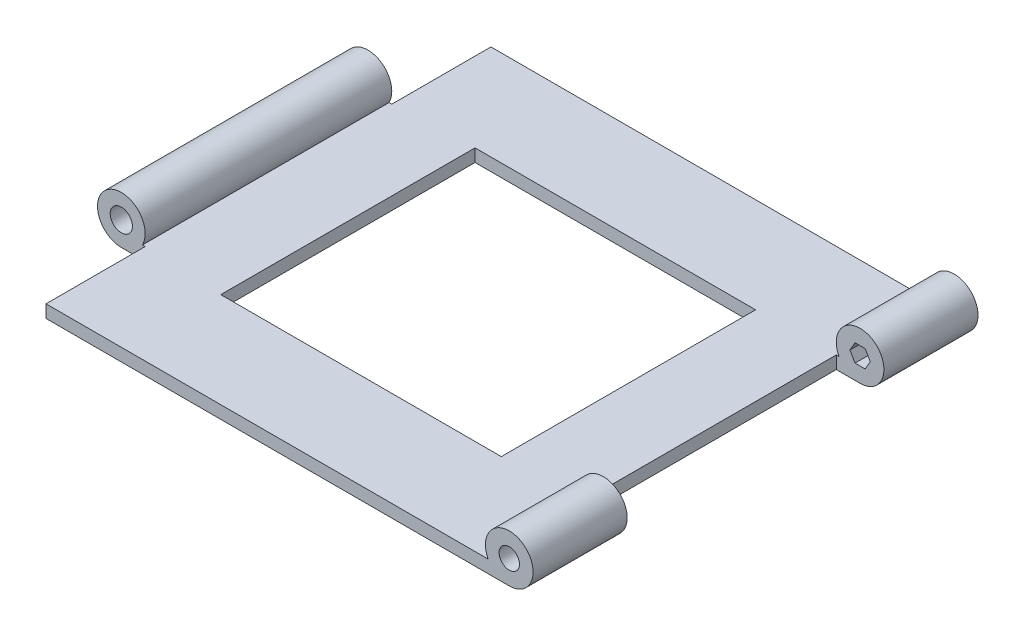
SolidWorks part; units mm, degrees
ref_plane "前视基准面" through (0, 0, 0) normal (0, 0, 1) x (1, 0, 0)
ref_plane "上视基准面" through (0, 0, 0) normal (0, 1, 0) x (1, 0, 0)
ref_plane "右视基准面" through (0, 0, 0) normal (1, 0, 0) x (0, 0, -1)
other "Configuration Table"
sketch "草图1" plane through (0, 0, 0) normal (0, 0, 1) x (1, 0, 0)
  line L0 (-77.4797, -5.3875) -> (75.7868, -5.3875)
  line L2 (69.1535, -1.3875) -> (-70.8465, -1.3875)
  line L4 (77.3868, 4.8838) -> (74.1868, 4.8838)
  line L5 (74.1868, 4.8838) -> (72.5868, 2.1125)
  line L6 (72.5868, 2.1125) -> (74.1868, -0.6588)
  line L7 (74.1868, -0.6588) -> (77.3868, -0.6588)
  line L8 (77.3868, -0.6588) -> (78.9868, 2.1125)
  line L9 (78.9868, 2.1125) -> (77.3868, 4.8838)
  arc A0 (-70.8465, -1.3875) -> (-77.4797, -5.3875) centre (-77.4797, 2.1125) ccw
  arc A1 (75.7868, -5.3875) -> (69.1535, -1.3875) centre (75.7868, 2.1125) ccw
  circle A2 centre (-77.4797, 2.1125) radius 3.5
  circle A3 centre (75.7868, 2.1125) radius 3.2 construction
  dimension "D1" = 4
  dimension "D2" = 7
  dimension "D3" = 6.4
  dimension "D4" = 4
  dimension "D6" = 4.3
  dimension "D5" = 140
extrude "凸台-拉伸1" add sketch "草图1" against normal blind 140
ref_plane "基准面1" through (-69.9797, 0, 0) normal (1, 0, 0) x (0, 0, -1)
sketch "草图2" plane through (-69.9797, 0, 0) normal (1, 0, 0) x (0, 0, -1)
  line L0 (140, 9.6125) -> (0, 9.6125) construction
  line L1 (0, -7.8675) -> (31.2, -7.8675)
  line L2 (0, -7.8675) -> (0, 9.6125)
  line L3 (0, 9.6125) -> (31.2, 9.6125)
  line L4 (31.2, -7.8675) -> (31.2, 9.6125)
  line L5 (140, 9.6125) -> (0, 9.6125) construction
  line L6 (70, 9.6125) -> (70, -10.9902) construction
  line L7 (140, 9.6125) -> (108.8, 9.6125)
  line L8 (108.8, -7.8675) -> (108.8, 9.6125)
  line L9 (140, -7.8675) -> (108.8, -7.8675)
  line L10 (140, -7.8675) -> (140, 9.6125)
  dimension "D1" = 31.2
extrude "切除-拉伸1" cut sketch "草图2" against normal blind 50
ref_plane "基准面2" through (68.2868, 0, 0) normal (-1, 0, 0) x (0, 0, 1)
sketch "草图3" plane through (68.2868, 0, 0) normal (-1, 0, 0) x (0, 0, 1)
  line L11 (-109.6, -19.073) -> (-30.4, -19.073)
  line L12 (-29.61, 22.4021) -> (-110.39, 22.4021)
  line L13 (-110.39, 22.4021) -> (-110.4, 22.4021)
  line L14 (-110.4, 22.4021) -> (-110.4, -19.073)
  line L15 (-110.4, -19.073) -> (-109.6, -19.073)
  line L16 (-70, 22.4021) -> (-70, -19.073) construction
  line L17 (-29.6, -19.073) -> (-30.4, -19.073)
  line L18 (-29.6, 22.4021) -> (-29.6, -19.073)
  line L19 (-29.61, 22.4021) -> (-29.6, 22.4021)
  line L20 (-140, 9.6125) -> (-140, -5.3875) construction
  line L21 (-140, 9.6125) -> (-140, -5.3875) construction
  line L22 (-140, 2.1125) -> (-110.4, 2.1125) construction
  line L23 (0, -5.3875) -> (0, 9.6125) construction
  line L24 (0, -5.3875) -> (0, 9.6125) construction
  line L25 (0, 2.1125) -> (-29.6, 2.1125) construction
  dimension "D1" = 0.01
  dimension "D2" = 29.6
extrude "切除-拉伸2" cut sketch "草图3" against normal blind 60
sketch "草图4" plane through (0, 0, -29.6) normal (0, 0, -1) x (-1, 0, 0)
  line L6 (-75.7868, -5.3875) -> (-68.2868, -5.3875)
  line L7 (-68.2868, -5.3875) -> (-68.2868, -1.3875)
  line L8 (-68.2868, -1.3875) -> (-69.1535, -1.3875)
  line L9 (-75.7868, -5.3875) -> (-68.2868, -5.3875) construction
  line L10 (-68.2868, -5.3875) -> (-68.2868, -1.3875) construction
  line L11 (-68.2868, -1.3875) -> (-69.1535, -1.3875) construction
  circle A1 centre (-75.7868, 2.1125) radius 3.2
  arc A2 (-69.1535, -1.3875) -> (-75.7868, -5.3875) centre (-75.7868, 2.1125) ccw
  arc A3 (-69.1535, -1.3875) -> (-75.7868, -5.3875) centre (-75.7868, 2.1125) ccw construction
  dimension "D1" = 0
extrude "切除-拉伸3" cut sketch "草图4" against normal through all
sketch "草图5" plane through (0, -5.3875, 0) normal (0, -1, 0) x (1, 0, 0)
  line L0 (-3.5515, -30) -> (-3.5515, 0) construction
  line L1 (-44.9797, -30) -> (43.2868, -30)
  line L2 (-44.9797, -30) -> (-44.9797, -110)
  line L3 (-44.9797, -110) -> (43.2868, -110)
  line L4 (43.2868, -30) -> (43.2868, -110)
  line L5 (-69.9797, 0) -> (75.7868, 0) construction
  line L6 (-3.5515, -110) -> (-3.5515, -140) construction
  line L7 (-69.9797, -140) -> (75.7868, -140) construction
  line L8 (-44.9797, -79.4275) -> (-69.9797, -79.4275) construction
  line L9 (-69.9797, -8.25) -> (-69.9797, 8.25) construction
  line L10 (43.2868, -80.6177) -> (68.2868, -80.6177) construction
  line L11 (68.2868, 8.25) -> (68.2868, -8.25) construction
  dimension "D1" = 30
  dimension "D2" = 25
extrude "切除-拉伸4" cut sketch "草图5" against normal through all
